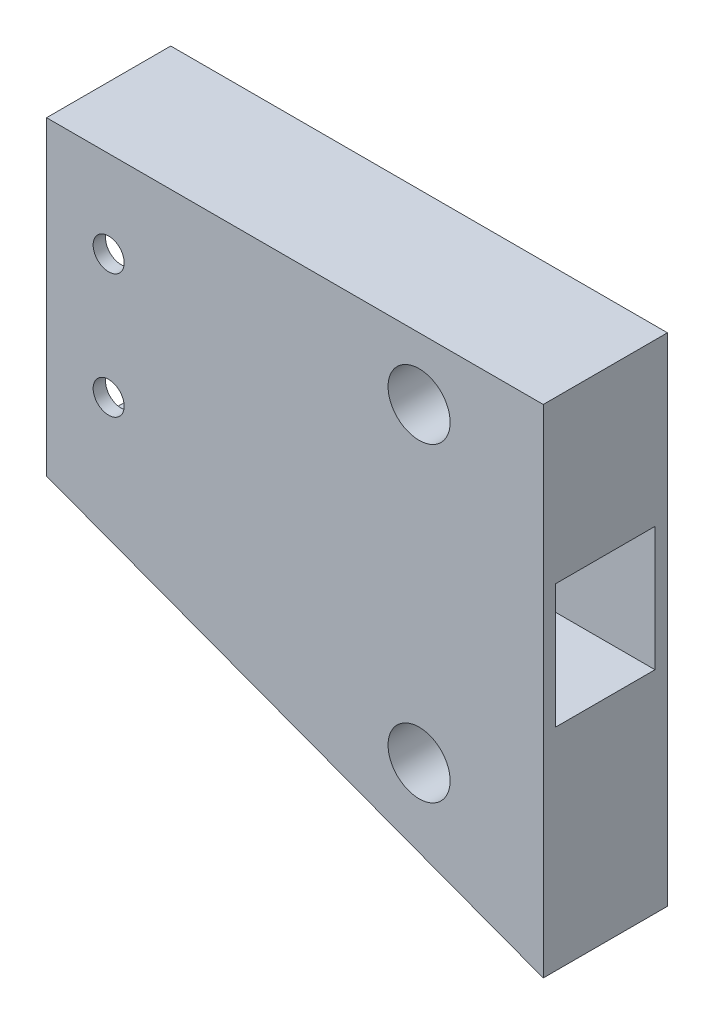
SolidWorks part; units mm, degrees
ref_plane "Front Plane" through (0, 0, 0) normal (0, 0, 1) x (1, 0, 0)
ref_plane "Top Plane" through (0, 0, 0) normal (0, 1, 0) x (1, 0, 0)
ref_plane "Right Plane" through (0, 0, 0) normal (1, 0, 0) x (0, 0, -1)
sketch "Sketch1" plane through (0, 0, 0) normal (0, 0, 1) x (1, 0, 0)
  line L0 (0, 0) -> (40, -15)
  line L1 (40, -15) -> (40, 25)
  line L2 (40, 25) -> (0, 25)
  line L3 (0, 25) -> (0, 0)
  dimension "D1" = 25
  dimension "D2" = 40
  dimension "D3" = 40
extrude "Boss-Extrude1" add sketch "Sketch1" along normal blind 10
sketch "Sketch2" plane through (0, 0, 0) normal (-1, 0, 0) x (0, 0, 1)
  line L0 (0, 25) -> (0, 0) construction
  line L1 (1, 22) -> (9, 22)
  line L2 (1, 22) -> (1, 2)
  line L3 (1, 2) -> (9, 2)
  line L4 (9, 22) -> (9, 2)
  line L5 (10, 25) -> (0, 25) construction
  dimension "D1" = 20
  dimension "D2" = 8
  dimension "D3" = 1
  dimension "D4" = 3
extrude "Cut-Extrude1" cut sketch "Sketch2" against normal blind 20
sketch "Sketch3" plane through (20, 0, 0) normal (-1, 0, 0) x (0, 0, 1)
  line L0 (9, 2) -> (9, 22) construction
  line L1 (1, 2) -> (9, 2)
  line L2 (1, 2) -> (1, 12)
  line L3 (1, 12) -> (9, 12)
  line L4 (9, 2) -> (9, 12)
  dimension "D1" = 10
extrude "Cut-Extrude2" cut sketch "Sketch3" against normal through all
sketch "Sketch4" plane through (0, 0, 10) normal (0, 0, 1) x (1, 0, 0)
  line L0 (40, 25) -> (0, 25) construction
  line L1 (40, -15) -> (40, 25) construction
  line L2 (0, 25) -> (0, 0) construction
  line L3 (0, 2) -> (0, 22) construction
  line L4 (0, 2) -> (0, 22)
  circle A0 centre (30, 20) radius 2.5
  circle A1 centre (30, -5) radius 2.5
  circle A2 centre (5, 18) radius 1.25
  circle A3 centre (5, 8) radius 1.25
  dimension "D1" = 5
  dimension "D5" = 2.5
  dimension "D2" = 5
  dimension "D3" = 10
  dimension "D6" = 5
  dimension "D7" = 4
  dimension "D8" = 10
  dimension "D4" = 2
extrude "Cut-Extrude3" cut sketch "Sketch4" against normal blind 10 contours A2 | A3 | A0 | A1
